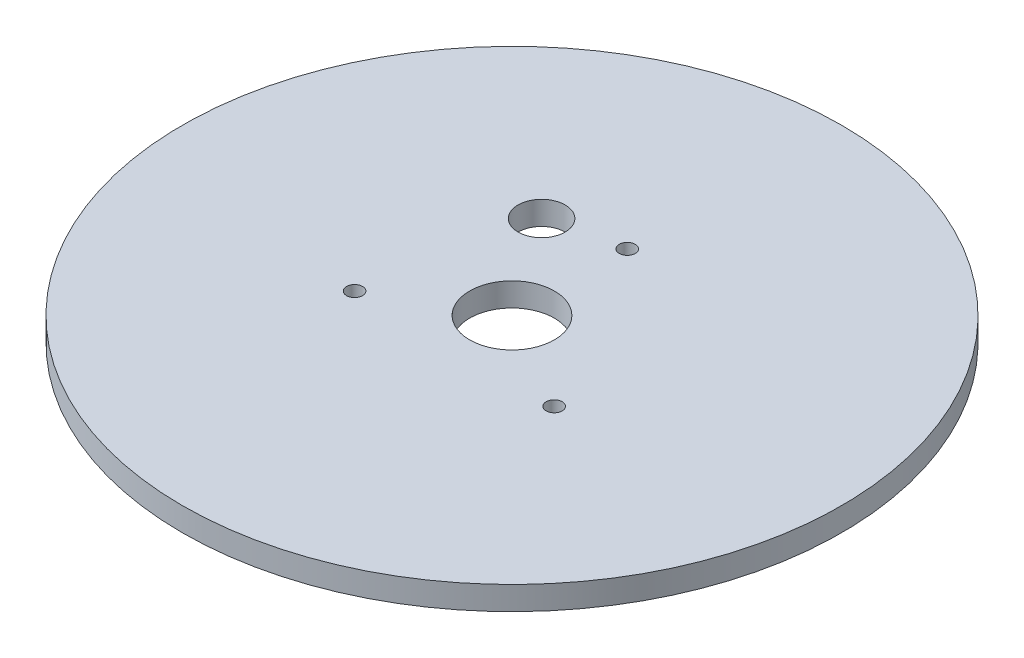
SolidWorks part; units mm, degrees
ref_plane "Front Plane" through (0, 0, 0) normal (0, 0, 1) x (1, 0, 0)
ref_plane "Top Plane" through (0, 0, 0) normal (0, 1, 0) x (1, 0, 0)
ref_plane "Right Plane" through (0, 0, 0) normal (1, 0, 0) x (0, 0, -1)
sketch "Sketch1" plane through (0, 0, 0) normal (0, 1, 0) x (1, 0, 0)
  line L0 (0, 28.93) -> (0, 11.43) construction
  line L1 (0, 0) -> (-25.0541, -14.465) construction
  line L2 (0, 0) -> (25.0541, -14.465) construction
  line L3 (26.9239, -15.5445) -> (25.0541, -14.465) construction
  line L4 (-26.9239, -15.5445) -> (-25.0541, -14.465) construction
  line L5 (0, 0) -> (-18.6481, 26.6323) construction
  circle A0 centre (0, 0) radius 88.9
  circle A1 centre (0, 0) radius 11.43
  circle A2 centre (0, 31.089) radius 2.159
  circle A3 centre (26.9239, -15.5445) radius 2.159
  circle A4 centre (-26.9239, -15.5445) radius 2.159
  circle A5 centre (-18.6481, 26.6323) radius 6.35
  dimension "D1" = 177.8
  dimension "D2" = 22.86
  dimension "D3" = 4.318
  dimension "D4" = 17.5
  dimension "D8" = 12.7
  dimension "D9" = 35
  dimension "D6" = 120
  dimension "D7" = 120
  dimension "D10" = 32.512
  dimension "D5" = 3
extrude "Boss-Extrude1" add sketch "Sketch1" along normal blind 6.35
